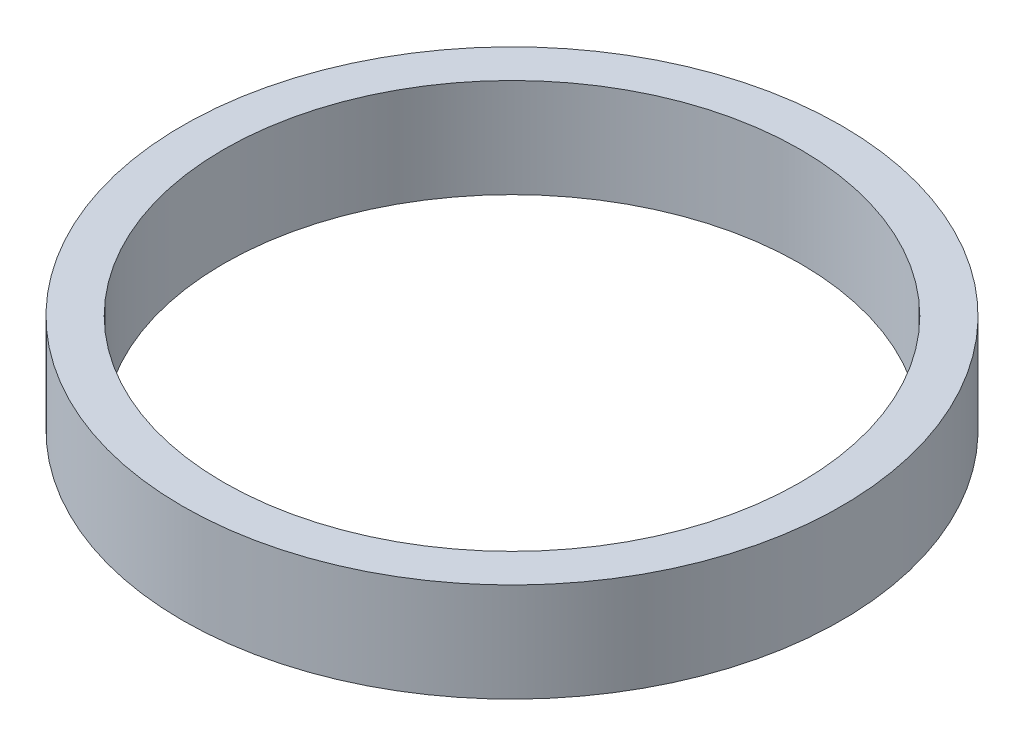
SolidWorks part; units mm, degrees
ref_plane "Спереди" through (0, 0, 0) normal (0, 0, 1) x (1, 0, 0)
ref_plane "Сверху" through (0, 0, 0) normal (0, 1, 0) x (1, 0, 0)
ref_plane "Справа" through (0, 0, 0) normal (1, 0, 0) x (0, 0, -1)
sketch "Эскиз1" plane through (0, 0, 0) normal (0, 1, 0) x (1, 0, 0)
  circle A0 centre (0, 0) radius 10
  circle A1 centre (0, 0) radius 8.75
  dimension "D1" = 17.5
  dimension "D2" = 20
extrude "Бобышка-Вытянуть1" add sketch "Эскиз1" along normal blind 3
